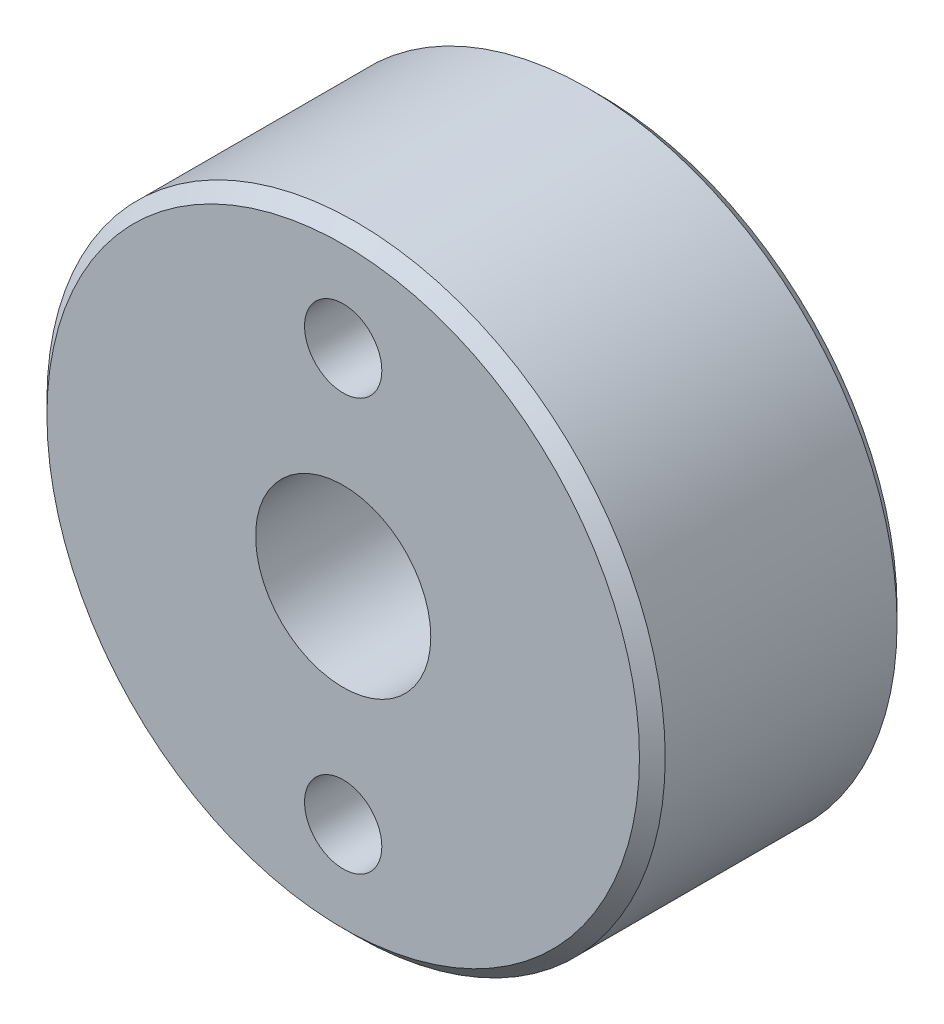
SolidWorks part; units mm, degrees
ref_plane "前视基准面" through (0, 0, 0) normal (0, 0, 1) x (1, 0, 0)
ref_plane "上视基准面" through (0, 0, 0) normal (0, 1, 0) x (1, 0, 0)
ref_plane "右视基准面" through (0, 0, 0) normal (1, 0, 0) x (0, 0, -1)
sketch "草图1" plane through (0, 0, 0) normal (0, 0, 1) x (1, 0, 0)
  circle A0 centre (0, 0) radius 12
  dimension "D1" = 24
extrude "凸台-拉伸1" add sketch "草图1" along normal blind 10
chamfer "倒角1" distance 0.5 angle 45 2 edges at (12, 0, 0) (12, 0, 10)
hole_wizard "M8 螺纹孔1" positions "草图3" profile "草图4" tap size "M8" standard "GB"
sketch "草图3" plane through (0, 0, 10) normal (0, 0, 1) x (1, 0, 0)
  point P0 (0, 0)
sketch "草图4" plane through (0, 0, 10) normal (1, 0, 0) x (0, -1, 0)
  line L0 (0, 0) -> (0, 19.75)
  line L1 (0, 19.75) -> (3.4, 17.7071)
  line L2 (3.4, 17.7071) -> (3.4, 0)
  line L5 (3.4, 0) -> (0, 0)
  line L10 (0, 19.75) -> (-3.4, 17.7071) construction
  line L11 (0, -6.35) -> (0, 107.95) construction
  dimension "螺纹孔钻头直径" = 6.8
  dimension "螺纹孔钻头深度" = 19.75
  dimension "导头角度" = 118
cosmetic thread "孔螺纹线1"
sketch "草图5" plane through (0, 0, 10) normal (0, 0, 1) x (1, 0, 0)
  line L0 (0, -5.5) -> (0, 5.5) construction
  circle A0 centre (0, 0) radius 8 construction
  point P1 (0, 8)
  point P2 (0, -8)
  point P5 (0, 0)
  dimension "D1" = 16
hole_wizard "Ø3.0mm 暗销孔1" positions "草图5" profile "草图6" hole size "Ø3.0" standard "GB"
sketch "草图6" plane through (0, -8, 10) normal (1, 0, 0) x (0, -1, 0)
  line L0 (0, 0) -> (0, 19.75)
  line L1 (0, 19.75) -> (1.5, 18.8487)
  line L2 (1.5, 18.8487) -> (1.5, 0)
  line L5 (1.5, 0) -> (0, 0)
  line L10 (0, 19.75) -> (-1.5, 18.8487) construction
  line L11 (0, -6.35) -> (0, 107.95) construction
  dimension "孔直径" = 3
  dimension "孔深度" = 19.75
  dimension "导头角度" = 118
